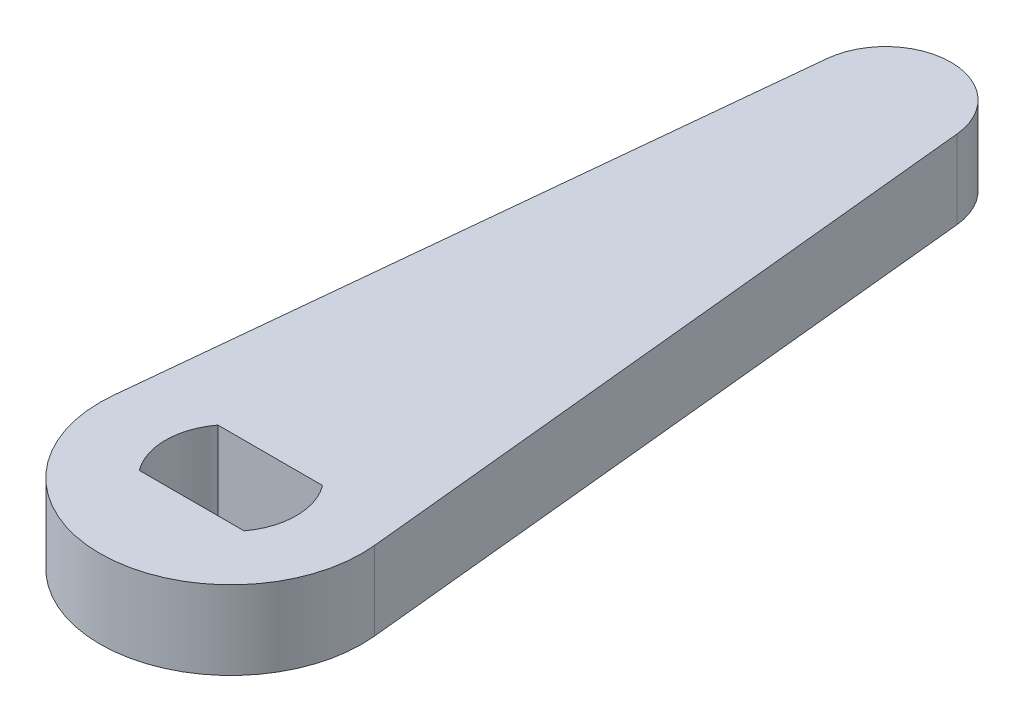
SolidWorks part; units mm, degrees
ref_plane "Front Plane" through (0, 0, 0) normal (0, 0, 1) x (1, 0, 0)
ref_plane "Top Plane" through (0, 0, 0) normal (0, 1, 0) x (1, 0, 0)
ref_plane "Right Plane" through (0, 0, 0) normal (1, 0, 0) x (0, 0, -1)
sketch "Sketch1" plane through (0, 0, 0) normal (0, 1, 0) x (1, 0, 0)
  line L0 (-4.9749, 0.5) -> (-2.4875, 25.25)
  line L1 (4.9749, 0.5) -> (2.4875, 25.25)
  line L2 (-2, -1.5) -> (2, -1.5)
  line L5 (-2, 1.5) -> (2, 1.5)
  line L6 (-2.1437, -1.2862) -> (2.1437, 1.2862) construction
  line L7 (2.1437, -1.2862) -> (-2.1437, 1.2862) construction
  arc A0 (-4.9749, 0.5) -> (4.9749, 0.5) centre (0, 0) ccw
  arc A2 (2.4875, 25.25) -> (-2.4875, 25.25) centre (0, 25) ccw
  arc A3 (-2, 1.5) -> (-2, -1.5) centre (0, 0) ccw
  arc A4 (2, -1.5) -> (2, 1.5) centre (0, 0) ccw
  dimension "D1" = 5
  dimension "D2" = 10
  dimension "D3" = 25
  dimension "D4" = 5
extrude "Boss-Extrude1" add sketch "Sketch1" along normal blind 3
